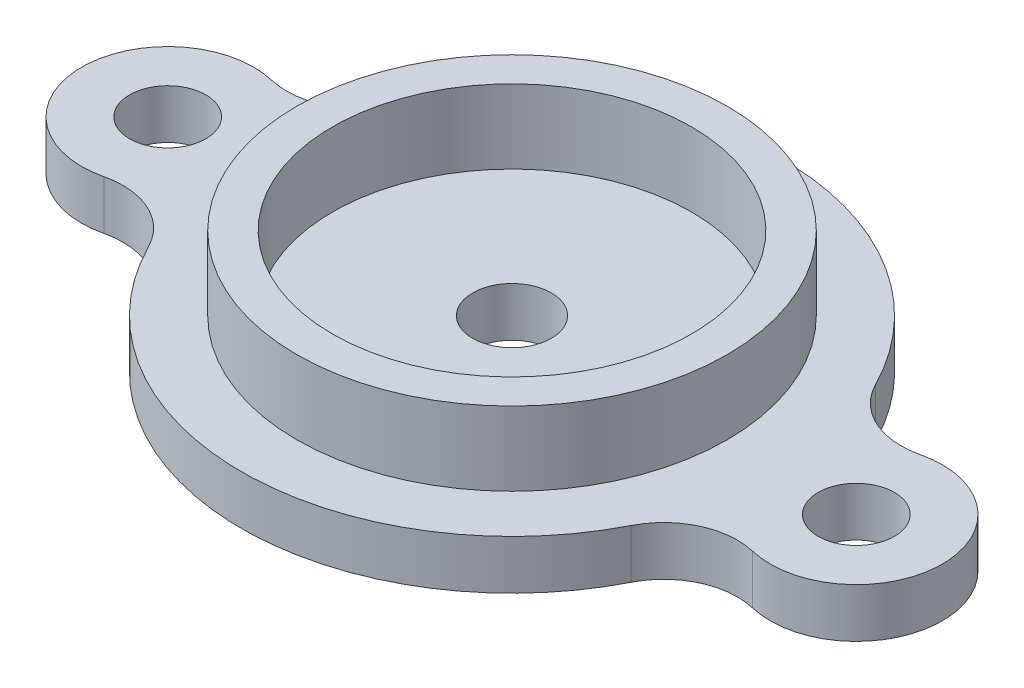
SolidWorks part; units mm, degrees
ref_plane "前视基准面" through (0, 0, 0) normal (0, 0, 1) x (1, 0, 0)
ref_plane "上视基准面" through (0, 0, 0) normal (0, 1, 0) x (1, 0, 0)
ref_plane "右视基准面" through (0, 0, 0) normal (1, 0, 0) x (0, 0, -1)
sketch "草图1" plane through (0, 0, 0) normal (0, 1, 0) x (1, 0, 0)
  circle A0 centre (0, 0) radius 11
  dimension "D1" = 22
extrude "凸台-拉伸1" add sketch "草图1" along normal blind 2
sketch "草图3" plane through (0, 2, 0) normal (0, 1, 0) x (1, 0, 0)
  line L0 (8.2948, 0) -> (-14, 0) construction
  line L1 (0, 6.8251) -> (0, -5.1418) construction
  arc A1 (13.1875, 3.4044) -> (9.8144, 4.9676) centre (12.4911, 6.3224) cw
  arc A3 (13.1875, 3.4044) -> (13.1875, -3.4044) centre (14, 0) cw
  circle A4 centre (0, 0) radius 11
  arc A5 (-9.8144, 4.9676) -> (-9.8144, -4.9676) centre (0, 0) ccw
  arc A6 (9.8144, 4.9676) -> (9.8144, -4.9676) centre (0, 0) cw
  arc A7 (13.1875, -3.4044) -> (9.8144, -4.9676) centre (12.4911, -6.3224) ccw
  circle A9 centre (-14, 0) radius 1.55 construction
  arc A10 (-13.1875, 3.4044) -> (-13.1875, -3.4044) centre (-14, 0) ccw construction
  arc A11 (-13.1875, 3.4044) -> (-9.8144, 4.9676) centre (-12.4911, 6.3224) ccw construction
  arc A12 (-13.1875, 3.4044) -> (-9.8144, 4.9676) centre (-12.4911, 6.3224) ccw
  arc A14 (-13.1875, -3.4044) -> (-9.8144, -4.9676) centre (-12.4911, -6.3224) cw
  circle A15 centre (14, 0) radius 1.55 construction
  arc A25 (-13.1875, 3.4044) -> (-13.1875, -3.4044) centre (-14, 0) ccw
  circle A28 centre (-14, 0) radius 1.55
  circle A29 centre (14, 0) radius 1.55
  dimension "D2" = 0
extrude "凸台-拉伸2" add sketch "草图3" against normal up to surface (2 mm away) up to face at (0, 0, 11)
sketch "草图4" plane through (0, 0, 0) normal (0, -1, 0) x (1, 0, 0)
  circle A0 centre (0, 0) radius 1.6
  dimension "D1" = 3.2
extrude "切除-拉伸1" cut sketch "草图4" against normal up to next
sketch "草图5" plane through (0, 2, 0) normal (0, 1, 0) x (1, 0, 0)
  circle A0 centre (0, 0) radius 7.3
  circle A1 centre (0, 0) radius 8.75
  dimension "D1" = 14.6
  dimension "D2" = 17.5
extrude "凸台-拉伸3" add sketch "草图5" along normal blind 3
